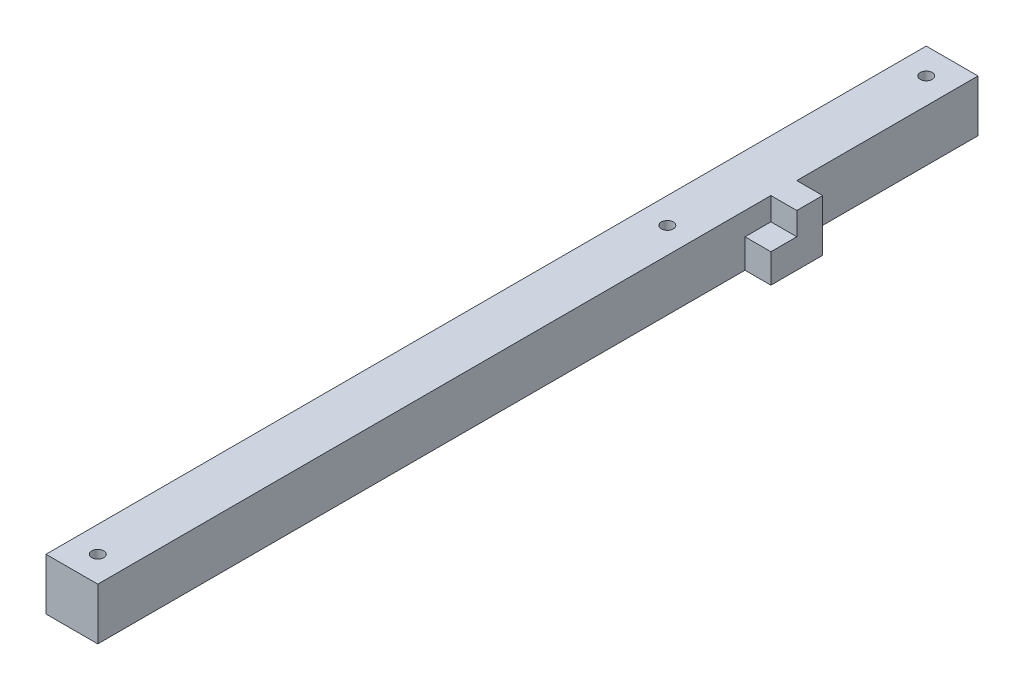
SolidWorks part; units mm, degrees
ref_plane "Front" through (0, 0, 0) normal (0, 0, 1) x (1, 0, 0)
ref_plane "Top" through (0, 0, 0) normal (0, 1, 0) x (1, 0, 0)
ref_plane "Right" through (0, 0, 0) normal (1, 0, 0) x (0, 0, -1)
sketch "Sketch18" plane through (0, 0, 0) normal (0, 1, 0) x (1, 0, 0)
  line L1 (-12.7, -12.7) -> (0, -12.7)
  line L2 (-12.7, -12.7) -> (-12.7, 203.2)
  line L3 (-12.7, 203.2) -> (0, 203.2)
  line L4 (0, -12.7) -> (0, 203.2)
  dimension "D1" = 12.7
  dimension "D2" = 12.7
  dimension "D3" = 12.7
  dimension "D4" = 215.9
extrude "Boss-Extrude3" add sketch "Sketch18" along normal blind 12.7
sketch "Sketch26" plane through (0, 12.7, 0) normal (0, 1, 0) x (1, 0, 0)
  line L0 (-6.35, -12.7) -> (-6.35, 203.2) construction
  line L1 (-12.7, -12.7) -> (0, -12.7) construction
  line L2 (0, 203.2) -> (-12.7, 203.2) construction
  point P6 (-6.35, 196.85)
  point P7 (-6.35, -6.35)
  point P8 (-6.35, 133.35)
  dimension "D1" = 6.35
  dimension "D2" = 6.35
  dimension "D3" = 63.5
hole_wizard "#32 (0.116) Diameter Hole7" positions "Sketch27" profile "Sketch28" hole size "#32" standard "ANSI Inch" end condition through all
sketch "Sketch27" plane through (0, 12.7, 0) normal (0, 1, 0) x (1, 0, 0)
  point P0 (-6.35, 196.85)
  point P3 (-6.35, 133.35)
  point P6 (-6.35, -6.35)
sketch "Sketch28" plane through (-6.35, 12.7, -196.85) normal (1, 0, 0) x (0, 0, 1)
  line L0 (0, 0) -> (0, 12.7)
  line L1 (0, 12.7) -> (1.4732, 12.7)
  line L2 (1.4732, 12.7) -> (1.4732, 0)
  line L5 (1.4732, 0) -> (0, 0)
  line L11 (0, -6.35) -> (0, 107.95) construction
  dimension "Thru Hole Dia." = 2.9464
  dimension "Thru Hole Depth" = 12.7
sketch "Sketch29" plane through (-12.7, 0, 0) normal (-1, 0, 0) x (0, 0, 1)
  line L0 (-203.2, 0) -> (12.7, 0) construction
  line L1 (-152.4, 0) -> (-158.75, 0)
  line L2 (-152.4, 0) -> (-152.4, 12.7)
  line L3 (-152.4, 12.7) -> (-158.75, 12.7)
  line L4 (-158.75, 0) -> (-158.75, 12.7)
  line L5 (-203.2, 12.7) -> (12.7, 12.7) construction
  line L6 (-203.2, 12.7) -> (-203.2, 0) construction
  dimension "D1" = 50.8
  dimension "D2" = 6.35
extrude "Boss-Extrude4" add sketch "Sketch29" along normal blind 6.35
sketch "Sketch30" plane through (-12.7, 0, 0) normal (-1, 0, 0) x (0, 0, 1)
  line L1 (-152.4, 0) -> (-146.05, 0)
  line L2 (-152.4, 0) -> (-152.4, 7.112)
  line L3 (-152.4, 7.112) -> (-146.05, 7.112)
  line L4 (-146.05, 0) -> (-146.05, 7.112)
  dimension "D1" = 7.112
  dimension "D2" = 6.35
extrude "Boss-Extrude5" add sketch "Sketch30" along normal blind 6.35
sketch "Sketch32" plane through (0, 0, 0) normal (0, -1, 0) x (1, 0, 0)
  line L0 (-6.35, -203.2) -> (-6.35, 12.7) construction
  line L1 (0, -203.2) -> (-12.7, -203.2) construction
  line L2 (-12.7, 12.7) -> (0, 12.7) construction
ref_plane "Plane1" through (-6.35, 0, 0) normal (-1, 0, 0) x (0, 0, 1)
mirror "Mirror2" about plane through (-6.35, 0, 0) normal (-1, 0, 0) of "Boss-Extrude5", "Boss-Extrude4"
sketch "Sketch33" plane through (-19.05, 0, 0) normal (-1, 0, 0) x (0, 0, 1)
  line L1 (-158.75, 12.7) -> (-146.05, 12.7)
  line L2 (-158.75, 12.7) -> (-158.75, 0)
  line L3 (-158.75, 0) -> (-146.05, 0)
  line L4 (-146.05, 12.7) -> (-146.05, 0)
extrude "Cut-Extrude1" cut sketch "Sketch33" against normal blind 6.35
